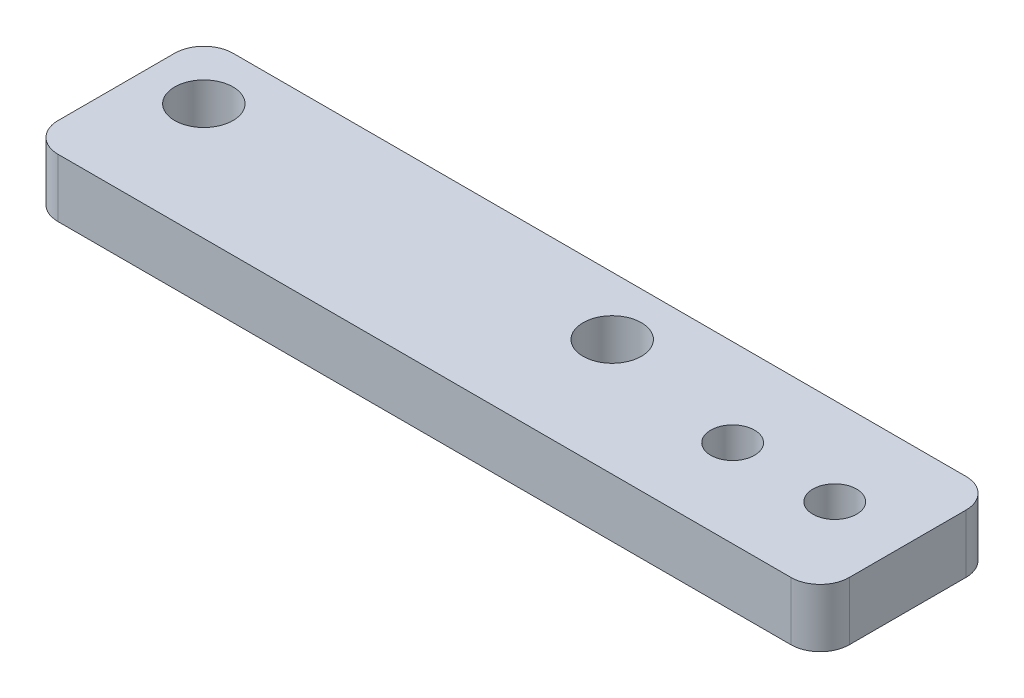
SolidWorks part; units mm, degrees
material "Stainless Steel (ferritic)"
ref_plane "Front Plane" through (0, 0, 0) normal (0, 0, 1) x (1, 0, 0)
ref_plane "Top Plane" through (0, 0, 0) normal (0, 1, 0) x (1, 0, 0)
ref_plane "Right Plane" through (0, 0, 0) normal (1, 0, 0) x (0, 0, -1)
sketch "Sketch1" plane through (0, 0, 0) normal (0, 1, 0) x (1, 0, 0)
  line L0 (-27.1284, 0) -> (27.1284, 0) construction
  line L1 (-27.1284, 6) -> (27.1284, 6)
  line L2 (-27.1284, 6) -> (-27.1284, -6)
  line L3 (-27.1284, -6) -> (27.1284, -6)
  line L4 (27.1284, 6) -> (27.1284, -6)
  line L5 (-27.1284, 6) -> (27.1284, -6) construction
  line L6 (-27.1284, -6) -> (27.1284, 6) construction
  line L7 (0, 6) -> (0, -6) construction
  line L8 (8.8716, 6) -> (8.8716, -6) construction
  line L9 (4.8716, 6) -> (4.8716, -6) construction
  line L10 (-23.1284, 6) -> (-23.1284, -6) construction
  line L11 (-27.1284, 5.61) -> (-23.1284, 5.61) construction
  line L12 (4.8716, 5.61) -> (8.8716, 5.61) construction
  circle A0 centre (15.1284, 0) radius 1.5
  circle A1 centre (22.1284, 0) radius 1.5
  circle A2 centre (-23.1284, 2) radius 2
  circle A3 centre (4.8716, 2) radius 2
  circle A4 centre (15.1284, 0) radius 2.84 construction
  circle A5 centre (4.8716, 2) radius 3.61 construction
  point P0 (0, 0)
  dimension "D1" = 3
  dimension "D2" = 3
  dimension "D6" = 4
  dimension "D7" = 4
  dimension "D10" = 5.68
  dimension "D11" = 7.22
  dimension "D12" = 4
  dimension "D3" = 7
  dimension "D4" = 5
  dimension "D5" = 12
  dimension "D8" = 28
  dimension "D9" = 36
  dimension "D13" = 4
extrude "Boss-Extrude1" add sketch "Sketch1" along normal blind 4
fillet "Fillet1" radius 2 4 edges at (-27.1284, 2, -6) (-27.1284, 2, 6) (27.1284, 2, -6) (27.1284, 2, 6)
